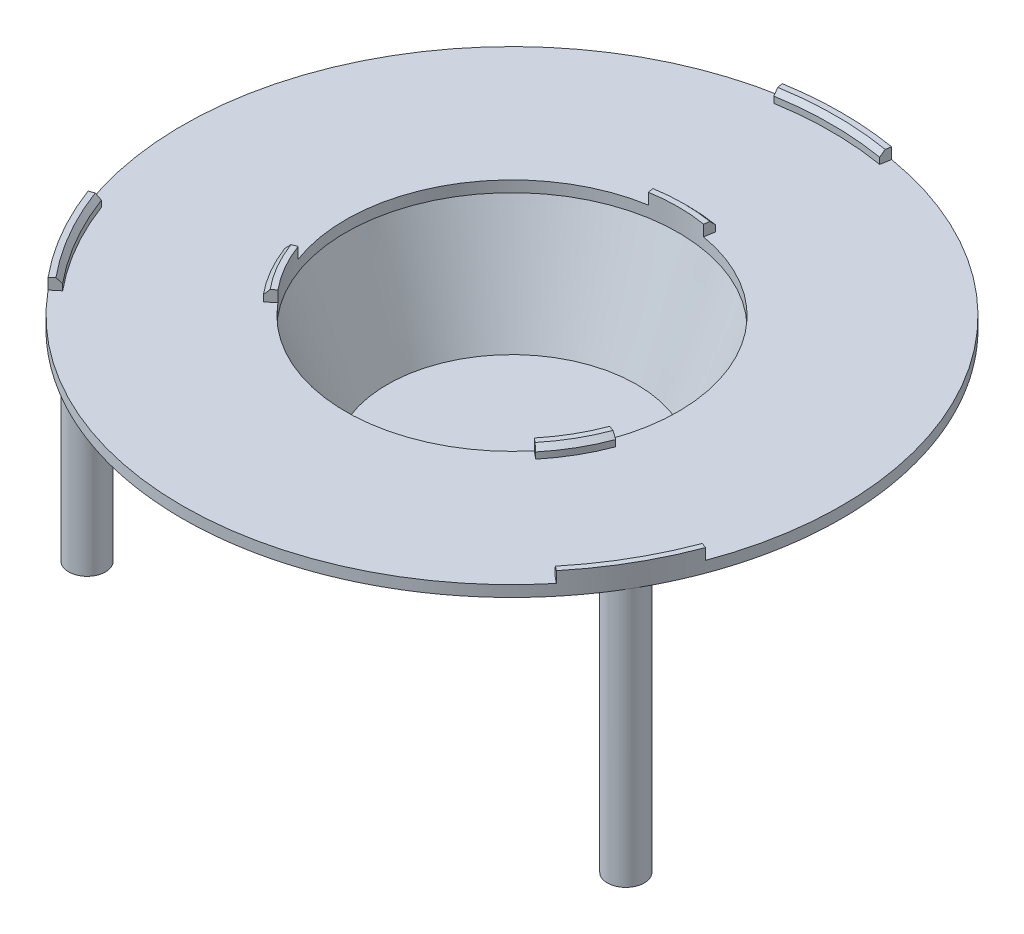
SolidWorks part; units mm, degrees
ref_plane "Front Plane" through (0, 0, 0) normal (0, 0, 1) x (1, 0, 0)
ref_plane "Top Plane" through (0, 0, 0) normal (0, 1, 0) x (1, 0, 0)
ref_plane "Right Plane" through (0, 0, 0) normal (1, 0, 0) x (0, 0, -1)
sketch "Sketch2" plane through (0, 0, 0) normal (0, 1, 0) x (1, 0, 0)
  circle A0 centre (0, 0) radius 66.04 construction
  circle A1 centre (0, 0) radius 56.007 construction
  circle A2 centre (0, 0) radius 48.006 construction
  circle A3 centre (0, 0) radius 76.2 construction
  circle A4 centre (0, 0) radius 86.2 construction
  circle A5 centre (0, 0) radius 45.006
  circle A6 centre (0, 0) radius 89.2
  circle A7 centre (0, 0) radius 47.806 construction
  circle A8 centre (0, 0) radius 86.4 construction
  dimension "D1" = 132.08
  dimension "D2" = 112.014
  dimension "D3" = 96.012
  dimension "D4" = 152.4
  dimension "D5" = 172.4
  dimension "D6" = 3
  dimension "D7" = 3
  dimension "D8" = 0.2
  dimension "D9" = 0.2
extrude "Boss-Extrude1" add sketch "Sketch2" along normal blind 3
sketch "Sketch3" plane through (0, 3, 0) normal (0, 1, 0) x (1, 0, 0)
  line L0 (0, 0) -> (-77.2495, -44.6) construction
  line L1 (0, 0) -> (77.2495, -44.6) construction
  line L2 (0, 0) -> (0, 89.2) construction
  line L3 (0, 0) -> (-15, 89.2) construction
  line L4 (0, 0) -> (15, 89.2) construction
  line L5 (15, 89.2) -> (-15, 89.2) construction
  line L6 (-69.7495, -57.5904) -> (-84.7495, -31.6096) construction
  line L7 (69.7495, -57.5904) -> (84.7495, -31.6096) construction
  line L8 (0, 0) -> (84.7495, -31.6096) construction
  line L9 (0, 0) -> (69.7495, -57.5904) construction
  line L10 (0, 0) -> (-69.7495, -57.5904) construction
  line L11 (-84.7495, -31.6096) -> (0, 0) construction
  line L12 (-34.7049, -28.655) -> (-36.8641, -30.4377)
  line L13 (-42.1684, -15.7279) -> (-44.7919, -16.7063)
  line L14 (-80.7652, -30.1236) -> (-83.576, -31.1719)
  line L15 (-14.328, 85.2037) -> (-14.7923, 87.9649)
  line L16 (14.328, 85.2037) -> (14.7923, 87.9649)
  line L17 (7.9278, 47.1441) -> (7.4635, 44.3828)
  line L18 (-7.9278, 47.1441) -> (-7.4635, 44.3828)
  line L19 (83.576, -31.1719) -> (80.9525, -30.1935)
  line L20 (68.7837, -56.793) -> (66.6246, -55.0102)
  line L21 (34.7049, -28.655) -> (36.8641, -30.4377)
  line L22 (42.1684, -15.7279) -> (44.7919, -16.7063)
  line L23 (-66.6246, -55.0102) -> (-68.7837, -56.793)
  circle A0 centre (0, 0) radius 89.2 construction
  arc A1 (-83.576, -31.1719) -> (-68.7837, -56.793) centre (0, 0) ccw
  circle A2 centre (0, 0) radius 45.006 construction
  arc A3 (34.7049, -28.655) -> (42.1684, -15.7279) centre (0, 0) ccw
  circle A4 centre (0, 0) radius 86.4 construction
  arc A5 (-80.9525, -30.1935) -> (-66.6246, -55.0102) centre (0, 0) ccw
  circle A6 centre (0, 0) radius 47.806 construction
  arc A7 (36.8641, -30.4377) -> (44.7919, -16.7063) centre (0, 0) ccw
  circle A8 centre (0, 0) radius 86.2 construction
  arc A9 (7.4635, 44.3828) -> (-7.4635, 44.3828) centre (0, 0) ccw
  arc A10 (7.9278, 47.1441) -> (-7.9278, 47.1441) centre (0, 0) ccw
  arc A11 (-44.7919, -16.7063) -> (-36.8641, -30.4377) centre (0, 0) ccw
  arc A12 (-42.1684, -15.7279) -> (-34.7049, -28.655) centre (0, 0) ccw
  arc A13 (68.7837, -56.793) -> (83.576, -31.1719) centre (0, 0) ccw
  arc A14 (66.6246, -55.0102) -> (80.9525, -30.1935) centre (0, 0) ccw
  arc A15 (14.7923, 87.9649) -> (-14.7923, 87.9649) centre (0, 0) ccw
  arc A16 (14.328, 85.2037) -> (-14.328, 85.2037) centre (0, 0) ccw
  point P13 (0, 89.2)
  point P14 (77.2495, -44.6)
  point P18 (-77.2495, -44.6)
  circle M11 centre (0, 0) radius 89.2
  circle M12 centre (0, 0) radius 45.006
  dimension "D1" = 120
  dimension "D2" = 120
  dimension "D3" = 30
extrude "Boss-Extrude2" add sketch "Sketch3" along normal blind 3 contours A5 L14 L23 M11 | L13 A11 L12 M12 | L21 A7 L22 M12 | A14 L20 L19 M11 | A16 L16 L15 M11 | L17 A10 L18 M12
chamfer "Chamfer1" distance 1.3 angle 45 6 edges at (41.4012, 6, 23.903) (74.8246, 6, 43.2) (-74.8246, 6, 43.2) (-41.4012, 6, 23.903) (0, 6, -47.806) (0, 6, -86.4)
sketch "Sketch4" plane through (0, 0, 0) normal (0, -1, 0) x (1, 0, 0)
  line L0 (0, 0) -> (-77.2495, 44.6) construction
  line L1 (0, 0) -> (0, -89.2) construction
  line L2 (0, 0) -> (77.2495, 44.6) construction
  circle A0 centre (-72.9193, 42.1) radius 5
  circle A2 centre (72.9193, 42.1) radius 5
  circle A3 centre (0, -84.2) radius 5
  circle A4 centre (0, 0) radius 89.2 construction
  circle A5 centre (0, 0) radius 89.2 construction
  point P12 (74.6514, 43.1)
  point P17 (0, 0)
  point P18 (-71.7929, 41.4496)
  point P19 (74.6514, 43.1)
  point P20 (0, 0)
  point P21 (0, 0)
  dimension "D1" = 10
extrude "Boss-Extrude3" add sketch "Sketch4" along normal blind 70
ref_plane "Plane1" through (0, -30, 0) normal (0, 1, 0) x (1, 0, 0)
sketch "Sketch5" plane through (0, -30, 0) normal (0, 1, 0) x (1, 0, 0)
  circle A0 centre (0, 0) radius 31.75 construction
  circle A1 centre (0, 0) radius 36.75
  circle A2 centre (0, 0) radius 33.75
  dimension "D1" = 63.5
  dimension "D2" = 5
  dimension "D3" = 2
sketch "Sketch6" plane through (0, 0, 0) normal (0, -1, 0) x (1, 0, 0)
  circle A0 centre (0, 0) radius 45.006 construction
  circle A1 centre (0, 0) radius 45.006
  circle A2 centre (0, 0) radius 48.006
  dimension "D1" = 3
sketch "Sketch7" plane through (0, 0, 0) normal (1, 0, 0) x (0, 0, -1)
  line L0 (0, -30) -> (0, -32.81)
  line L1 (33.75, -30) -> (-33.75, -30) construction
  line L2 (0, -32.81) -> (-35.6957, -32.81)
  line L3 (0, -30) -> (-33.75, -30)
  line L4 (36.75, -30) -> (-36.75, -30) construction
  line L5 (0, -30) -> (-33.75, -30)
  line L6 (-45.006, 0) -> (-33.75, -30)
  line L7 (-48.006, 0) -> (48.006, 0)
  line L8 (-48.006, 0) -> (48.006, 0) construction
  line L9 (-45.006, 0) -> (45.006, 0)
  line L10 (-45.006, 0) -> (45.006, 0) construction
  line L11 (-48.006, 0) -> (-35.6957, -32.81)
  line L12 (-33.75, -30) -> (-36.3798, -30.9867) construction
  line L13 (-48.006, 0) -> (-45.006, 0)
  line L14 (0, -30) -> (0, 0) construction
  dimension "D1" = 0
  dimension "D3" = 2.81
  dimension "D2" = 0
revolve "Revolve1" add sketch "Sketch7" angle 360 about L14
